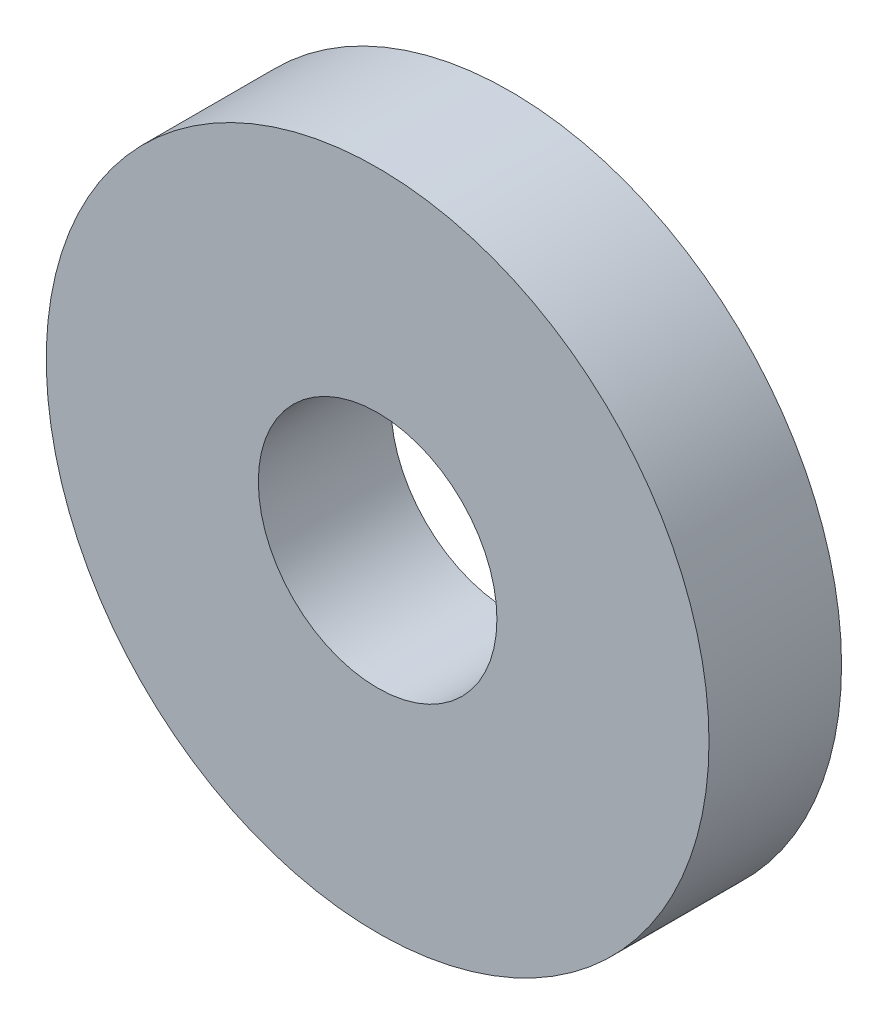
SolidWorks part; units mm, degrees
ref_plane "Piano frontale" through (0, 0, 0) normal (0, 0, 1) x (1, 0, 0)
ref_plane "Piano superiore" through (0, 0, 0) normal (0, 1, 0) x (1, 0, 0)
ref_plane "Piano destro" through (0, 0, 0) normal (1, 0, 0) x (0, 0, -1)
sketch "Schizzo1" plane through (0, 0, 0) normal (0, 0, 1) x (1, 0, 0)
  circle A0 centre (0, 0) radius 12.5
  circle A1 centre (0, 0) radius 4.5
  dimension "D1" = 25
  dimension "D2" = 9
extrude "Estrusione-Estrusione1" add sketch "Schizzo1" along normal blind 5
